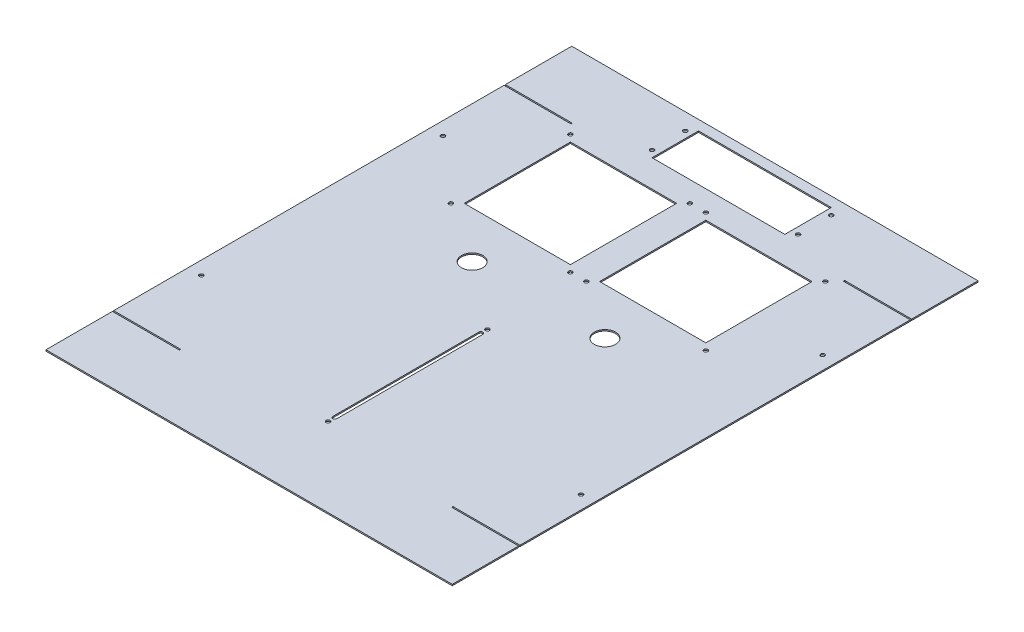
SolidWorks part; units mm, degrees
ref_plane "Front Plane" through (0, 0, 0) normal (0, 0, 1) x (1, 0, 0)
ref_plane "Top Plane" through (0, 0, 0) normal (0, 1, 0) x (1, 0, 0)
ref_plane "Right Plane" through (0, 0, 0) normal (1, 0, 0) x (0, 0, -1)
sketch "Sketch1" plane through (0, 0, 0) normal (0, 1, 0) x (1, 0, 0)
  line L1 (-153, -198) -> (153, -198)
  line L2 (-153, -198) -> (-153, 198)
  line L3 (-153, 198) -> (153, 198)
  line L4 (153, -198) -> (153, 198)
  line L5 (-153, -198) -> (153, 198) construction
  line L6 (-153, 198) -> (153, -198) construction
  point P0 (0, 0)
  dimension "D1" = 306
  dimension "D2" = 396
extrude "Boss-Extrude1" add sketch "Sketch1" along normal blind 1
sketch "Sketch2" plane through (0, 1, 0) normal (0, 1, 0) x (1, 0, 0)
  line L0 (0, 0) -> (0, -163.7017) construction
  line L2 (0, -23.5) -> (0, -133.5) construction
  line L3 (1.5, -23.5) -> (1.5, -133.5)
  line L4 (-1.5, -23.5) -> (-1.5, -133.5)
  circle A0 centre (0, -18.5) radius 1.5
  circle A1 centre (0, -138.5) radius 1.5
  arc A2 (1.5, -23.5) -> (-1.5, -23.5) centre (0, -23.5) ccw
  arc A3 (-1.5, -133.5) -> (1.5, -133.5) centre (0, -133.5) ccw
  point P11 (0, -78.5)
  dimension "D1" = 3
  dimension "D2" = 3
  dimension "D3" = 120
  dimension "D5" = 3
  dimension "D6" = 5
  dimension "D7" = 5
  dimension "D8" = 18.5
extrude "Cut-Extrude1" cut sketch "Sketch2" against normal through all
sketch "Sketch3" plane through (0, 1, 0) normal (0, 1, 0) x (1, 0, 0)
  circle A0 centre (-50, 20) radius 8
  dimension "D1" = 16
  dimension "D2" = 50
  dimension "D3" = 20
extrude "Cut-Extrude2" cut sketch "Sketch3" against normal through all
mirror "Mirror1" about plane through (0, 0, 0) normal (1, 0, 0) of "Cut-Extrude2"
sketch "Sketch4" plane through (0, 1, 0) normal (0, 1, 0) x (1, 0, 0)
  line L0 (0, 0) -> (0, 159.2972) construction
  line L1 (0, 140) -> (-111.1486, 140) construction
  line L2 (0, 50) -> (-116.9642, 50) construction
  line L3 (-96, 151.7636) -> (-96, 50) construction
  line L4 (-6, 153.6452) -> (-6, 50) construction
  line L6 (-91, 135) -> (-11, 135)
  line L7 (-91, 135) -> (-91, 55)
  line L8 (-91, 55) -> (-11, 55)
  line L9 (-11, 135) -> (-11, 55)
  circle A0 centre (-96, 140) radius 1.5
  circle A1 centre (-6, 140) radius 1.5
  circle A2 centre (-96, 50) radius 1.5
  circle A3 centre (-6, 50) radius 1.5
  dimension "D1" = 3
  dimension "D2" = 3
  dimension "D5" = 3
  dimension "D6" = 3
  dimension "D3" = 90
  dimension "D4" = 90
  dimension "D7" = 6
  dimension "D8" = 50
  dimension "D9" = 5
  dimension "D10" = 5
  dimension "D11" = 80
extrude "Cut-Extrude3" cut sketch "Sketch4" against normal through all
mirror "Mirror2" about plane through (0, 0, 0) normal (1, 0, 0) of "Cut-Extrude3"
sketch "Sketch6" plane through (0, 1, 0) normal (0, 1, 0) x (1, 0, 0)
  line L0 (-153, 147.5) -> (-103, 147.5) construction
  line L1 (-153, 148) -> (-103, 148)
  line L2 (-153, 147) -> (-103, 147)
  line L3 (-153, 198) -> (-153, -198) construction
  line L4 (153, 198) -> (-153, 198) construction
  arc A0 (-153, 148) -> (-153, 147) centre (-153, 147.5) ccw
  arc A1 (-103, 147) -> (-103, 148) centre (-103, 147.5) ccw
  circle A2 centre (-96, 140) radius 1.5 construction
  circle A3 centre (-143, 91) radius 1.5
  point P2 (-128, 147.5)
  dimension "D3" = 7
  dimension "D6" = 3
  dimension "D1" = 1
  dimension "D2" = 50
  dimension "D4" = 7
  dimension "D5" = 50
  dimension "D7" = 91
  dimension "D8" = 10
extrude "Cut-Extrude4" cut sketch "Sketch6" against normal through all
mirror "Mirror3" about plane through (0, 0, 0) normal (0, 0, 1) of "Cut-Extrude4"
mirror "Mirror4" about plane through (0, 0, 0) normal (1, 0, 0) of "Mirror3", "Cut-Extrude4"
sketch "Sketch8" plane through (0, 1, 0) normal (0, 1, 0) x (1, 0, 0)
  line L0 (0, 126.3898) -> (0, 208.0058) construction
  line L1 (153, 198) -> (-153, 198) construction
  line L2 (50, 190.5) -> (-50, 190.5)
  line L3 (50, 190.5) -> (50, 155.5)
  line L4 (50, 155.5) -> (-50, 155.5)
  line L5 (-50, 190.5) -> (-50, 155.5)
  line L6 (50, 190.5) -> (-50, 155.5) construction
  line L7 (50, 155.5) -> (-50, 190.5) construction
  circle A0 centre (-55, 185.5) radius 1.5
  circle A1 centre (-55, 160.5) radius 1.5
  circle A2 centre (55, 160.5) radius 1.5
  circle A3 centre (55, 185.5) radius 1.5
  point P3 (0, 173)
  dimension "D4" = 3
  dimension "D7" = 3
  dimension "D1" = 25
  dimension "D2" = 100
  dimension "D3" = 35
  dimension "D5" = 5
  dimension "D6" = 5
  dimension "D8" = 5
  dimension "D9" = 5
extrude "Cut-Extrude6" cut sketch "Sketch8" against normal through all
